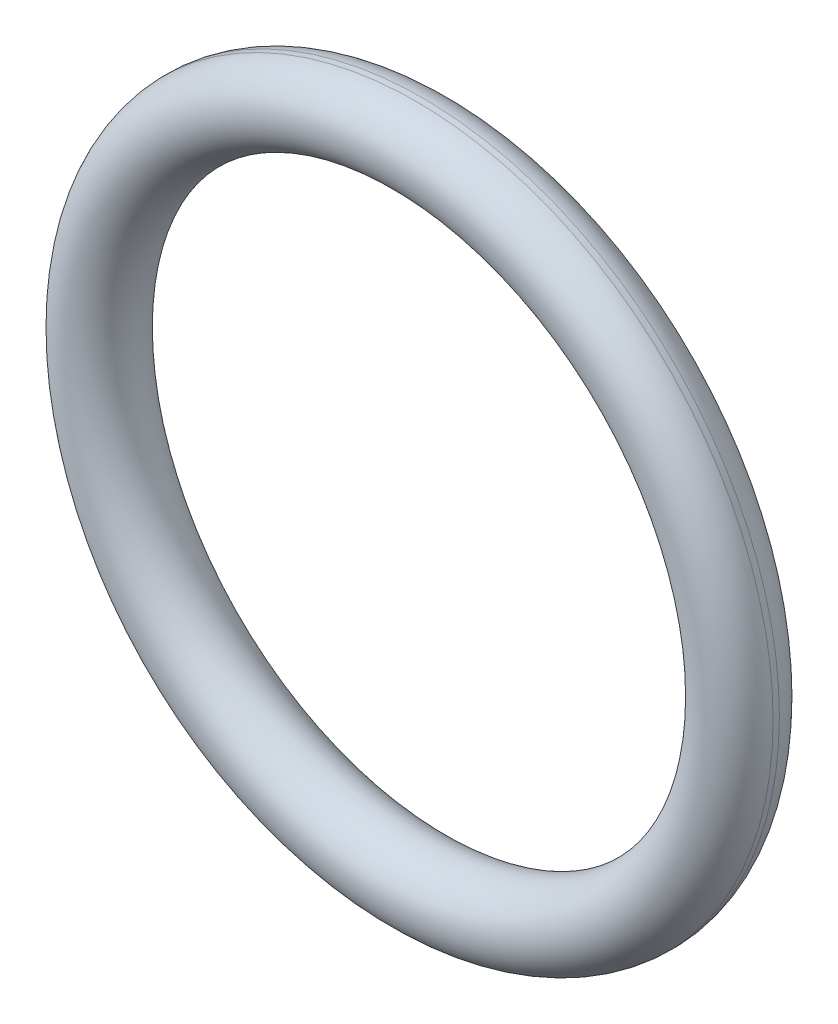
SolidWorks part; units mm, degrees
ref_plane "Front Plane" through (0, 0, 0) normal (0, 0, 1) x (1, 0, 0)
ref_plane "Top Plane" through (0, 0, 0) normal (0, 1, 0) x (1, 0, 0)
ref_plane "Right Plane" through (0, 0, 0) normal (1, 0, 0) x (0, 0, -1)
sketch "Sketch1" plane through (0, 0, 0) normal (1, 0, 0) x (0, 0, -1)
  line L0 (0, 0) -> (0, 25.5104) construction
  line L1 (-0.25, 28.5) -> (0.25, 28.5)
  line L2 (0, 0) -> (10.014, 0) construction
  arc A0 (-0.25, 28.5) -> (0.25, 28.5) centre (0, 25.5104) ccw
  dimension "D2" = 3
  dimension "D1" = 28.5
  dimension "D3" = 0.5
revolve "Revolve1" add sketch "Sketch1" angle 360 about L2
